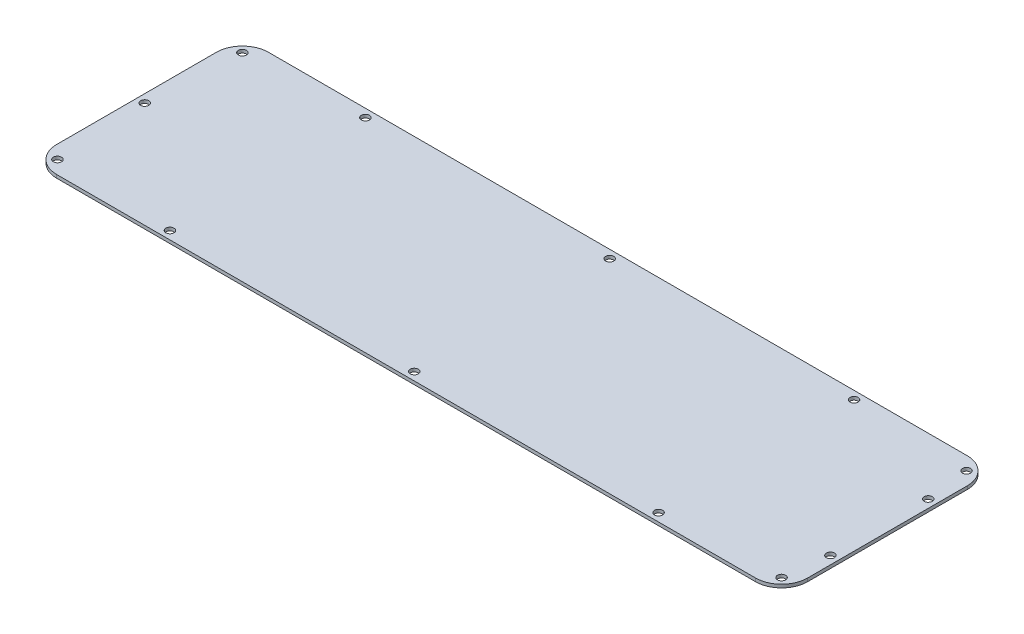
SolidWorks part; units mm, degrees
material "Acrylic (Medium-high impact)"
ref_plane "Front Plane" through (0, 0, 0) normal (0, 0, 1) x (1, 0, 0)
ref_plane "Top Plane" through (0, 0, 0) normal (0, 1, 0) x (1, 0, 0)
ref_plane "Right Plane" through (0, 0, 0) normal (1, 0, 0) x (0, 0, -1)
sketch "Sketch1" plane through (0, 0, 0) normal (0, 1, 0) x (1, 0, 0)
  line L1 (-230.5, 65) -> (230.5, 65)
  line L2 (-230.5, 65) -> (-230.5, -65)
  line L3 (-230.5, -65) -> (230.5, -65)
  line L4 (230.5, 65) -> (230.5, -65)
  line L5 (-230.5, 65) -> (230.5, -65) construction
  line L6 (-230.5, -65) -> (230.5, 65) construction
  point P0 (0, 0)
  dimension "D1" = 461
  dimension "D2" = 130
extrude "Boss-Extrude1" add sketch "Sketch1" along normal blind 2
fillet "Fillet1" radius 16 4 edges at (-230.5, 1, -65) (230.5, 1, -65) (230.5, 1, 65) (-230.5, 1, 65)
sketch "Sketch2" plane through (0, 2, 0) normal (0, 1, 0) x (1, 0, 0)
  line L20 (214.5, 60) -> (-214.5, 60)
  line L21 (225.5, -49) -> (225.5, 49)
  line L22 (-214.5, -60) -> (214.5, -60)
  line L23 (-225.5, 49) -> (-225.5, -49)
  line L24 (214.5, 60) -> (-214.5, 60)
  line L25 (225.5, -49) -> (225.5, 49)
  line L26 (-214.5, -60) -> (214.5, -60)
  line L27 (-225.5, 49) -> (-225.5, -49)
  arc A24 (225.5, 49) -> (214.5, 60) centre (214.5, 49) ccw
  arc A25 (214.5, -60) -> (225.5, -49) centre (214.5, -49) ccw
  arc A26 (-225.5, -49) -> (-214.5, -60) centre (-214.5, -49) ccw
  arc A27 (-214.5, 60) -> (-225.5, 49) centre (-214.5, 49) ccw
  arc A28 (225.5, 49) -> (214.5, 60) centre (214.5, 49) ccw
  arc A29 (214.5, -60) -> (225.5, -49) centre (214.5, -49) ccw
  arc A30 (-225.5, -49) -> (-214.5, -60) centre (-214.5, -49) ccw
  arc A31 (-214.5, 60) -> (-225.5, 49) centre (-214.5, 49) ccw
  point P0 (-222.2782, 56.7782)
  point P1 (0, 60)
  point P2 (0, -60)
  point P3 (-222.2782, -56.7782)
  point P4 (222.2782, -56.7782)
  point P5 (222.2782, 56.7782)
  point P6 (150, 60)
  point P7 (-150, 60)
  point P8 (-225.5, 0)
  point P9 (225.5, 0)
  point P10 (150, -60)
  point P12 (-150, -60)
  point P24 (225.5, 30)
  point P25 (225.5, -30)
  dimension "D6" = 30
  dimension "D2" = 150
  dimension "D3" = 150
  dimension "D4" = 150
  dimension "D5" = 150
  dimension "D7" = 30
  dimension "D8" = 451
  dimension "D1" = 5
hole_wizard "Ø5.0 (5) Diameter Hole1" positions "3DSketch1" profile "Sketch3" hole size "Ø5.0" standard "DIN" end condition through all
sketch3d "3DSketch1"
  point P0 (-222.2782, 2, -56.7782)
  point P3 (-150, 2, -60)
  point P6 (-225.5, 2, 0)
  point P9 (-222.2782, 2, 56.7782)
  point P12 (-150, 2, 60)
  point P15 (0, 2, -60)
  point P18 (0, 2, 60)
  point P21 (150, 2, 60)
  point P24 (150, 2, -60)
  point P27 (222.2782, 2, -56.7782)
  point P33 (222.2782, 2, 56.7782)
  point P36 (225.5, 2, -30)
  point P39 (225.5, 2, 30)
sketch "Sketch3" plane through (-222.2782, 2, -56.7782) normal (1, 0, 0) x (0, 0, 1)
  line L0 (0, 0) -> (0, 2)
  line L1 (0, 2) -> (2.5, 2)
  line L2 (2.5, 2) -> (2.5, 0)
  line L5 (2.5, 0) -> (0, 0)
  line L11 (0, -6.35) -> (0, 107.95) construction
  dimension "Thru Hole Dia." = 5
  dimension "Thru Hole Depth" = 2
